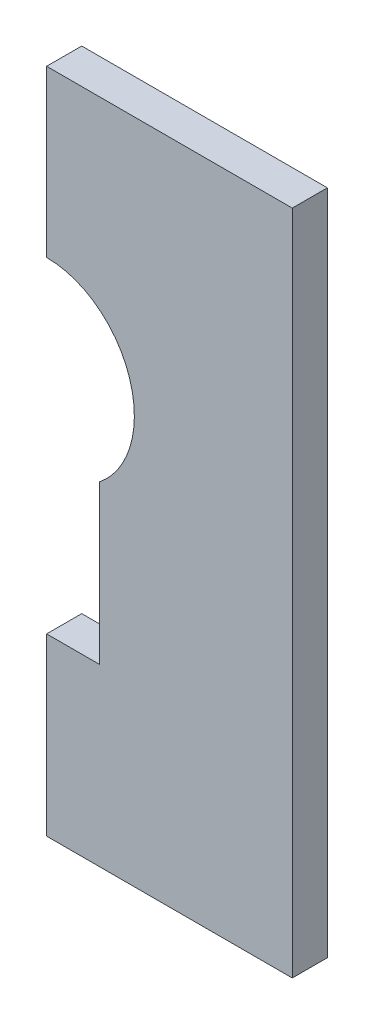
SolidWorks part; units mm, degrees
ref_plane "Plan de face" through (0, 0, 0) normal (0, 0, 1) x (1, 0, 0)
ref_plane "Plan de dessus" through (0, 0, 0) normal (0, 1, 0) x (1, 0, 0)
ref_plane "Plan de droite" through (0, 0, 0) normal (1, 0, 0) x (0, 0, -1)
sketch "Esquisse1" plane through (0, 0, 0) normal (0, 0, 1) x (1, 0, 0)
  line L1 (0, 0) -> (70, 0)
  line L2 (0, 0) -> (0, 190)
  line L3 (0, 190) -> (70, 190)
  line L4 (70, 0) -> (70, 190)
  point P7 (0, 0)
  dimension "D1" = 70
  dimension "D2" = 190
extrude "Boss.-Extru.1" add sketch "Esquisse1" along normal blind 10
ref_plane "Plan1" through (0, 0, 0) normal (0, -0.342, -0.9397) x (1, 0, 0)
sketch "Esquisse2" plane through (0, 0, 0) normal (0, -0.342, -0.9397) x (1, 0, 0)
  line L0 (0, -80.7785) -> (0, -130.7785)
  line L2 (70, -178.5416) -> (0, -178.5416) construction
  line L4 (0, -178.5416) -> (0, 0) construction
  arc A0 (0, -80.7785) -> (0, -130.7785) centre (0, -105.7785) cw
  point P0 (0, -105.7785)
  dimension "D2" = 25
  dimension "D1" = 72.7631
extrude "Enlèv. mat.-Extru.1" cut sketch "Esquisse2" against normal through all
sketch "Esquisse3" plane through (0, 0, 0) normal (0, 0, -1) x (-1, 0, 0)
  line L0 (0, 85.9627) -> (0, 0) construction
  line L1 (0, 49.9233) -> (-15, 49.9233)
  line L2 (0, 49.9233) -> (0, 94.9233)
  line L3 (0, 94.9233) -> (-15, 94.9233)
  line L4 (-15, 49.9233) -> (-15, 94.9233)
  ellipse E0 centre (0, 116.2068) end of major axis (0, 89.6024) minor radius 25 (0, 142.8113) -> (0, 89.6024) ccw construction
  dimension "D1" = 45
  dimension "D2" = 15
extrude "Enlèv. mat.-Extru.2" cut sketch "Esquisse3" against normal through all
